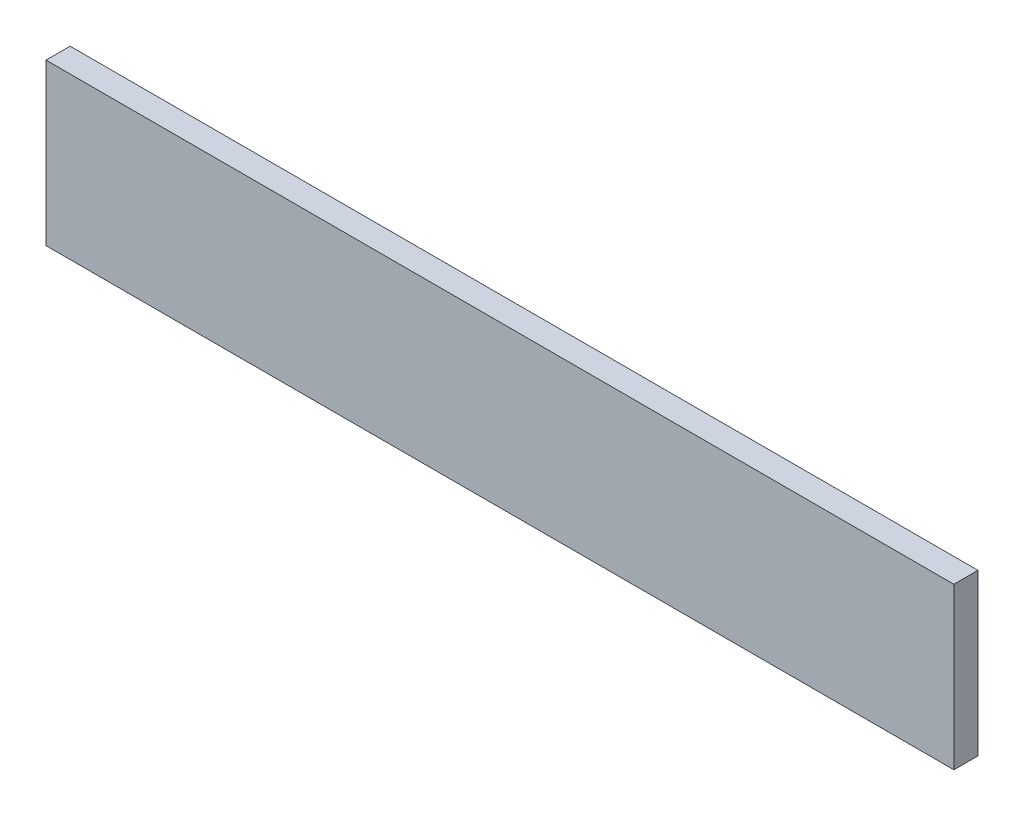
SolidWorks part; units mm, degrees
material "Pine"
ref_plane "Front Plane" through (0, 0, 0) normal (0, 0, 1) x (1, 0, 0)
ref_plane "Top Plane" through (0, 0, 0) normal (0, 1, 0) x (1, 0, 0)
ref_plane "Right Plane" through (0, 0, 0) normal (1, 0, 0) x (0, 0, -1)
sketch "Sketch1" plane through (0, 0, 0) normal (0, 0, 1) x (1, 0, 0)
  line L1 (0, 0) -> (717.55, 0)
  line L2 (0, 0) -> (0, 127)
  line L3 (0, 127) -> (717.55, 127)
  line L4 (717.55, 0) -> (717.55, 127)
  dimension "D1" = 717.55
  dimension "D2" = 127
extrude "Boss-Extrude1" add sketch "Sketch1" along normal blind 19.05
